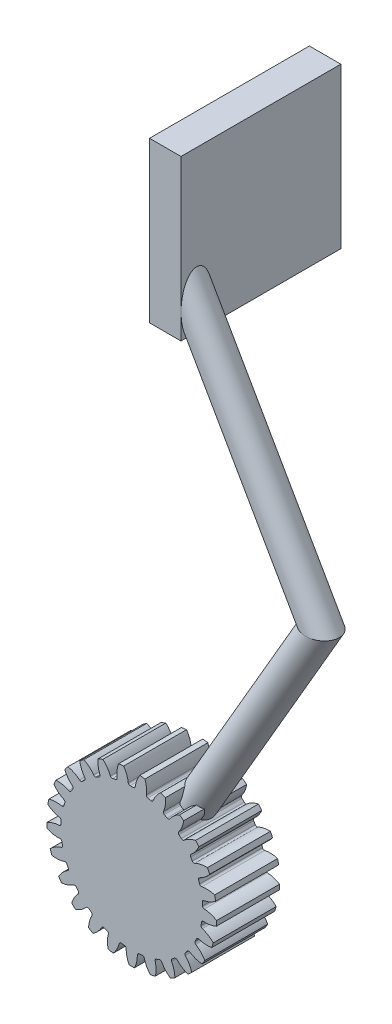
SolidWorks part; units mm, degrees
ref_plane "Front Plane" through (0, 0, 0) normal (0, 0, 1) x (1, 0, 0)
ref_plane "Top Plane" through (0, 0, 0) normal (0, 1, 0) x (1, 0, 0)
ref_plane "Right Plane" through (0, 0, 0) normal (1, 0, 0) x (0, 0, -1)
sketch "Sketch1" plane through (0, 0, 0) normal (0, 0, 1) x (1, 0, 0)
  circle A0 centre (0, 0) radius 27
  circle A1 centre (0, 0) radius 25
  circle A2 centre (0, 0) radius 22.5
  dimension "D1" = 45
  dimension "D2" = 50
  dimension "D3" = 54
extrude "Boss-Extrude1" add sketch "Sketch1" along normal mid plane 20 contours A2 | A1 A2 | A0 A1
sketch "Sketch2" plane through (0, 0, 0) normal (0, 0, 1) x (1, 0, 0)
  line L0 (0, -31.4954) -> (0, 43.6882) construction
  line L1 (0, 43.6882) -> (0, -31.4954) construction
  line L2 (1.5698, 24.9507) -> (-1.5698, 24.9507) construction
  line L3 (0, 0) -> (-1.072, 22.4744) construction
  line L4 (0, 20.6378) -> (-2.6344, 27.8758) construction
  line L5 (0, 0) -> (3.5093, 27.7792) construction
  line L6 (1.5698, 24.9507) -> (4.6845, 24.5572) construction
  arc A1 (-3.3153, 27.803) -> (-1.072, 22.4744) centre (-9.4743, 22.0737) cw
  circle A2 centre (0, 0) radius 28
  circle A3 centre (0, 0) radius 28
  circle A4 centre (0, 0) radius 22.5 construction
  circle A5 centre (0, 0) radius 27 construction
  circle A6 centre (0, 0) radius 25 construction
  circle A7 centre (0, 0) radius 22.5
  circle A8 centre (0, 0) radius 27
  circle A9 centre (0, 0) radius 25
  arc A10 (3.3153, 27.803) -> (1.072, 22.4744) centre (9.4743, 22.0737) ccw
  dimension "D2" = 20
  dimension "D3" = 7.2
  dimension "D1" = 1
extrude "Cut-Extrude2" cut sketch "Sketch2" against normal through all both and the other way through all contours A10 A3 A1 A8 | A10 A8 A1 A9 | A10 A9 A1 A7
fillet "Fillet1" radius 0.6 2 edges at (-1.072, 22.4744, 0) (1.072, 22.4744, 0)
pattern_circular "CirPattern1" count 25 over 360 about axis through (0, 0, 0) along (0, 0, 1) of "Cut-Extrude2", "Fillet1"
scale "Scale1" scale about centroid uniform scaling yes scale factor 0.5
sketch "Sketch4" plane through (0, 0, 0) normal (0, 0, 1) x (1, 0, 0)
  line L0 (0, 0) -> (25.0982, 43.2444)
  line L1 (25.0982, 43.2444) -> (0.325, 86.6758)
  line L2 (-12.375, 0) -> (-12.375, 108.0073) construction
  circle A0 centre (0, 0) radius 12.375
  dimension "D1" = 24.75
  dimension "D2" = 12.7
  dimension "D3" = 50
  dimension "D4" = 50
ref_plane "Plane1" through (0.325, 86.6758, 0) normal (-0.4955, 0.8686, 0) x (0.8686, 0.4955, 0)
sketch "Sketch5" plane through (0.325, 86.6758, 0) normal (-0.4955, 0.8686, 0) x (0.8686, 0.4955, 0)
  circle A0 centre (0, 0) radius 2.5
  dimension "D1" = 5
sweep "Sweep1" add profiles "Sketch5" path "Sketch4"
sketch "Sketch7" plane through (0, 0, 0) normal (0, 0, 1) x (1, 0, 0)
  line L9 (0.325, 86.6758) -> (-8.7076, 86.6758)
  line L10 (0.325, 86.6758) -> (0.325, 78.7373)
  line L11 (0.325, 78.7373) -> (-8.7076, 78.7373)
  line L12 (-8.7076, 86.6758) -> (-8.7076, 78.7373)
extrude "Cut-Extrude3" cut sketch "Sketch7" against normal through all both and the other way through all
sketch "Sketch8" plane through (0.325, 0, 0) normal (-1, 0, 0) x (0, 0, 1)
  line L1 (-22.9, 73.9758) -> (2.5, 73.9758)
  line L2 (-22.9, 73.9758) -> (-22.9, 99.3758)
  line L3 (-22.9, 99.3758) -> (2.5, 99.3758)
  line L4 (2.5, 73.9758) -> (2.5, 99.3758)
  line L5 (-22.9, 73.9758) -> (2.5, 99.3758) construction
  line L6 (-22.9, 99.3758) -> (2.5, 73.9758) construction
  point P0 (0, 87.5047)
  point P5 (0, 0)
  point P6 (0, 0)
  dimension "D1" = 25.4
  dimension "D2" = 25.4
extrude "Boss-Extrude2" add sketch "Sketch8" against normal blind 5
equation "\"m\"= 2mm'module"
equation "\"p\"= 20'pressure angle"
equation "\"n\"= 25'number of teeth"
equation "\"d\"= \"n\" * \"m\"'pitch circle diameter"
equation "\"o\"= \"m\" * ( \"n\" + 2 )'addendum circle diameter"
equation "\"i\"= \"o\" - \"m\" * IIF ( \"m\" = > 1.25 , 2.25 , 2.4 ) * 2'dedendum circle diameter"
equation "\"D1@Sketch1\"=\"i\""
equation "\"D2@Sketch1\"=\"d\""
equation "\"D3@Sketch1\"=\"o\""
equation "\"D2@Sketch2\"=\"p\""
equation "\"D3@Sketch2\"=180/\"n\""
equation "\"D1@Fillet1\"=.3*\"m\""
equation "\"D1@CirPattern1\"=\"n\""
